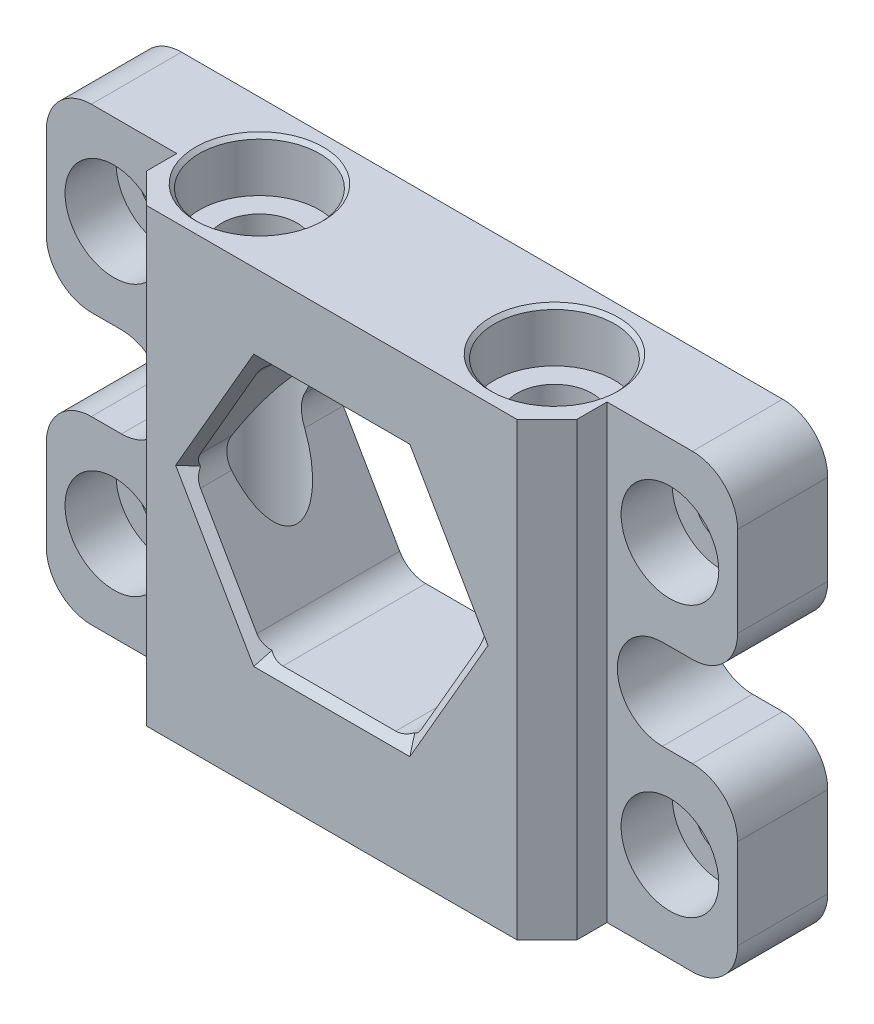
SolidWorks part; units mm, degrees
ref_plane "Front Plane" through (0, 0, 0) normal (0, 0, 1) x (1, 0, 0)
ref_plane "Top Plane" through (0, 0, 0) normal (0, 1, 0) x (1, 0, 0)
ref_plane "Right Plane" through (0, 0, 0) normal (1, 0, 0) x (0, 0, -1)
sketch "Sketch1" plane through (0, 0, 0) normal (0, 0, 1) x (1, 0, 0)
  line L1 (0, 0) -> (46, 0)
  line L2 (0, 0) -> (0, 30)
  line L3 (0, 30) -> (46, 30)
  line L4 (46, 0) -> (46, 30)
  dimension "D1" = 30
  dimension "D2" = 46
extrude "Boss-Extrude1" add sketch "Sketch1" along normal blind 10
sketch "Sketch2" plane through (0, 0, 10) normal (0, 0, 1) x (1, 0, 0)
  line L0 (23, 30) -> (23, 0) construction
  line L1 (27.9075, 24.5) -> (18.0925, 24.5)
  line L2 (18.0925, 24.5) -> (13.185, 16)
  line L3 (13.185, 16) -> (18.0925, 7.5)
  line L4 (18.0925, 7.5) -> (27.9075, 7.5)
  line L5 (27.9075, 7.5) -> (32.815, 16)
  line L6 (32.815, 16) -> (27.9075, 24.5)
  line L7 (46, 30) -> (0, 30) construction
  line L8 (0, 0) -> (46, 0) construction
  circle A0 centre (23, 16) radius 8.5 construction
  dimension "D1" = 5.5
  dimension "D2" = 17
extrude "Cut-Extrude1" cut sketch "Sketch2" against normal through all
sketch "Sketch3" plane through (0, 30, 0) normal (0, 1, 0) x (1, 0, 0)
  line L0 (32.815, 0) -> (32.815, -10) construction
  line L1 (32.815, 0) -> (32.815, -10)
  line L2 (13.185, 0) -> (13.185, -10) construction
  line L3 (13.185, 0) -> (13.185, -10)
  point P0 (13.185, -5)
  point P2 (32.815, -5)
hole_wizard "CBORE for M5 Hex Socket Head Cap Screw1" positions "Sketch3" profile "Sketch4" counterbore size "M5" standard "DIN"
sketch "Sketch4" plane through (13.185, 30, 5) normal (1, 0, 0) x (0, 0, 1)
  line L0 (0, 0) -> (0, 27)
  line L1 (0, 27) -> (2.5, 25.4978)
  line L2 (2.5, 25.4978) -> (2.5, 3.5)
  line L3 (2.5, 3.5) -> (4, 3.5)
  line L5 (4, 3.5) -> (4, 0.25)
  line L6 (4, 0.25) -> (4.25, 0)
  line L7 (4.25, 0) -> (0, 0)
  line L8 (-4, 0.25) -> (-4.25, 0) construction
  line L10 (0, 27) -> (-2.5, 25.4978) construction
  line L11 (0, -6.35) -> (0, 107.95) construction
  dimension "Hole Dia." = 5
  dimension "Hole Depth" = 27
  dimension "C'Bore Dia." = 8
  dimension "C'Bore Depth" = 3.5
  dimension "Near C'Sink Dia." = 8.5
  dimension "Near C'Sink Angle" = 90
  dimension "Drill Angle" = 118
sketch "Sketch5" plane through (0, 0, 10) normal (0, 0, 1) x (1, 0, 0)
  line L0 (0, 30) -> (0, 0) construction
  line L1 (46, 0) -> (46, 30) construction
  line L2 (46, 30) -> (0, 30) construction
  line L3 (0, 0) -> (46, 0) construction
  point P0 (4.5, 24)
  point P6 (41.5, 24)
  point P7 (41.5, 6)
  point P8 (4.5, 6)
  dimension "D3" = 4.5
  dimension "D4" = 4.5
  dimension "D5" = 6
  dimension "D6" = 6
  dimension "D1" = 2
  dimension "D2" = 2
hole_wizard "CBORE for M3 Hex Socket Head Cap Screw1" positions "Sketch5" profile "Sketch6" counterbore size "M3" standard "DIN" end condition through all
sketch "Sketch6" plane through (4.5, 24, 10) normal (1, 0, 0) x (0, -1, 0)
  line L0 (0, 0) -> (0, 10)
  line L1 (0, 10) -> (1.7, 10)
  line L3 (1.7, 10) -> (1.7, 3.4)
  line L4 (3.25, 3.4) -> (1.7, 3.4)
  line L5 (3.25, 3.4) -> (3.25, 0.025)
  line L6 (3.25, 0.025) -> (3.275, 0)
  line L7 (3.275, 0) -> (0, 0)
  line L8 (-3.25, 0.025) -> (-3.275, 0) construction
  line L11 (0, -6.35) -> (0, 107.95) construction
  dimension "Thru Hole Dia." = 3.4
  dimension "Thru Hole Depth" = 10
  dimension "C'Bore Dia." = 6.5
  dimension "C'Bore Depth" = 3.4
  dimension "Near C'Sink Dia." = 6.55
  dimension "Near C'Sink Angle" = 90
sketch "Sketch9" plane through (0, 0, 0) normal (0, -1, 0) x (-1, 0, 0)
  circle A0 centre (-13.185, -5) radius 2.5 construction
  circle A1 centre (-32.815, -5) radius 2.5 construction
  circle A2 centre (-13.185, -5) radius 2.5
  circle A3 centre (-32.815, -5) radius 2.5
  point P1 (-13.185, -5)
  point P3 (-32.815, -5)
hole_wizard "Tap Drill for M3 Helicoil1" positions "Sketch9" profile "Sketch10" hole size "M3x0.5" standard "DIN"
sketch "Sketch10" plane through (13.185, 0, 5) normal (1, 0, 0) x (0, 0, -1)
  line L0 (0, 0) -> (0, 25)
  line L1 (0, 25) -> (1.575, 24.0536)
  line L2 (1.575, 24.0536) -> (1.575, 0.025)
  line L3 (1.575, 0.025) -> (1.6, 0)
  line L5 (1.6, 0) -> (0, 0)
  line L6 (-1.575, 0.025) -> (-1.6, 0) construction
  line L10 (0, 25) -> (-1.575, 24.0536) construction
  line L11 (0, -6.35) -> (0, 107.95) construction
  dimension "Hole Dia." = 3.15
  dimension "Hole Depth" = 25
  dimension "Near C'Sink Dia." = 3.2
  dimension "Near C'Sink Angle" = 90
  dimension "Drill Angle" = 118
sketch "Sketch11" plane through (0, 0, 10) normal (0, 0, 1) x (1, 0, 0)
  line L4 (0, 15) -> (46, 15) construction
  line L9 (0, 30) -> (0, 0) construction
  line L10 (46, 0) -> (46, 30) construction
  line L11 (23, 15) -> (23, 20.7966) construction
  line L12 (5, 18) -> (0, 18)
  line L13 (0, 18) -> (0, 12)
  line L14 (0, 12) -> (5, 12)
  line L15 (0, 18) -> (0, 12)
  line L16 (46, 18) -> (46, 12)
  line L17 (41, 18) -> (46, 18)
  line L18 (46, 12) -> (41, 12)
  arc A3 (5, 12) -> (5, 18) centre (5, 15) ccw
  arc A4 (41, 12) -> (41, 18) centre (41, 15) cw
  line M18 (46, 0) -> (46, 30)
  line M22 (0, 30) -> (0, 0)
  dimension "D1" = 5
  dimension "D2" = 6
extrude "Cut-Extrude2" cut sketch "Sketch11" against normal through all contours L14 A3 L12 M22 | A4 L18 L17 M18
sketch "Sketch13" plane through (0, 0, 10) normal (0, 0, 1) x (1, 0, 0)
  line L0 (15.685, 26.5) -> (10.685, 26.5) construction
  line L1 (15.685, 26.5) -> (10.685, 26.5) construction
  line L2 (10.685, 26.5) -> (8.685, 26.5) construction
  line L3 (8.685, 30) -> (8.685, 0)
  line L4 (23, 7.5) -> (23, 15) construction
  line L5 (18.0925, 7.5) -> (27.9075, 7.5) construction
  line L13 (41, 12) -> (46, 12)
  line L14 (46, 18) -> (41, 18)
  line L15 (0, 12) -> (0, 0)
  line L16 (0, 0) -> (46, 0)
  line L17 (0, 12) -> (0, 0)
  line L18 (46, 27) -> (46, 18)
  line L19 (37.315, 30) -> (46, 30)
  line L20 (37.315, 30) -> (37.315, 0)
  line L21 (46, 30) -> (0, 30)
  line L22 (46, 0) -> (37.315, 0)
  line L23 (46, 12) -> (46, 3)
  line L26 (0, 0) -> (8.685, 0)
  line L31 (8.685, 30) -> (0, 30)
  line L38 (46, 0) -> (46, 12)
  line L40 (5, 12) -> (0, 12)
  line L41 (5, 12) -> (0, 12)
  line L42 (46, 12) -> (41, 12)
  line L44 (41, 18) -> (46, 18)
  line L46 (0, 18) -> (5, 18)
  line L47 (0, 18) -> (5, 18)
  line L55 (46, 0) -> (46, 12)
  line L56 (46, 18) -> (46, 30)
  line L57 (46, 18) -> (46, 30)
  line L58 (0, 30) -> (0, 18)
  line L59 (0, 30) -> (0, 18)
  arc A5 (41, 12) -> (41, 18) centre (41, 15) cw
  arc A6 (46, 30) -> (46, 27) centre (43.4019, 28.5) cw
  arc A7 (46, 3) -> (46, 0) centre (43.4019, 1.5) cw
  arc A18 (5, 12) -> (5, 18) centre (5, 15) ccw
  arc A19 (5, 12) -> (5, 18) centre (5, 15) ccw
  arc A30 (41, 18) -> (41, 12) centre (41, 15) ccw
  dimension "D1" = 2
  dimension "D2" = 0
extrude "Cut-Extrude3" cut sketch "Sketch13" against normal blind 4
sketch "Sketch14" plane through (0, 0, 6) normal (0, 0, 1) x (1, 0, 0)
  point P0 (4.5, 24)
  point P3 (4.5, 6)
  point P7 (41.5, 24)
  point P10 (41.5, 6)
hole_wizard "CBORE for M3 Hex Socket Head Cap Screw2" positions "Sketch14" profile "Sketch15" counterbore size "M3" standard "DIN" end condition through all
sketch "Sketch15" plane through (4.5, 24, 6) normal (1, 0, 0) x (0, -1, 0)
  line L0 (0, 0) -> (0, 6)
  line L1 (0, 6) -> (1.7, 6)
  line L3 (1.7, 6) -> (1.7, 3.4)
  line L4 (1.7, 3.4) -> (3.25, 3.4)
  line L5 (3.25, 3.4) -> (3.25, 0)
  line L7 (3.25, 0) -> (0, 0)
  line L11 (0, -6.35) -> (0, 107.95) construction
  dimension "Thru Hole Dia." = 3.4
  dimension "Thru Hole Depth" = 6
  dimension "C'Bore Dia." = 6.5
  dimension "C'Bore Depth" = 3.4
chamfer "Chamfer1" distance 2 angle 45 2 edges at (8.685, 15, 10) (37.315, 15, 10)
chamfer "Chamfer2" distance 0.5 angle 45 6 edges at (30.3612, 20.25, 10) (30.3612, 11.75, 10) (23, 7.5, 10) (15.6388, 11.75, 10) (23, 24.5, 10) (15.6388, 20.25, 10)
fillet "Fillet2" radius 2 8 edges at (32.815, 16, 8.5) (32.815, 16, 1.25) (27.9075, 7.5, 4.75) (18.0925, 7.5, 4.75) (13.185, 16, 1.25) (13.185, 16, 8.5) (18.0925, 24.5, 4.75) (27.9075, 24.5, 4.75)
fillet "Fillet1" radius 3 8 edges at (46, 30, 3) (46, 0, 3) (0, 0, 3) (0, 30, 3) (46, 12, 3) (46, 18, 3) (0, 12, 3) (0, 18, 3)
